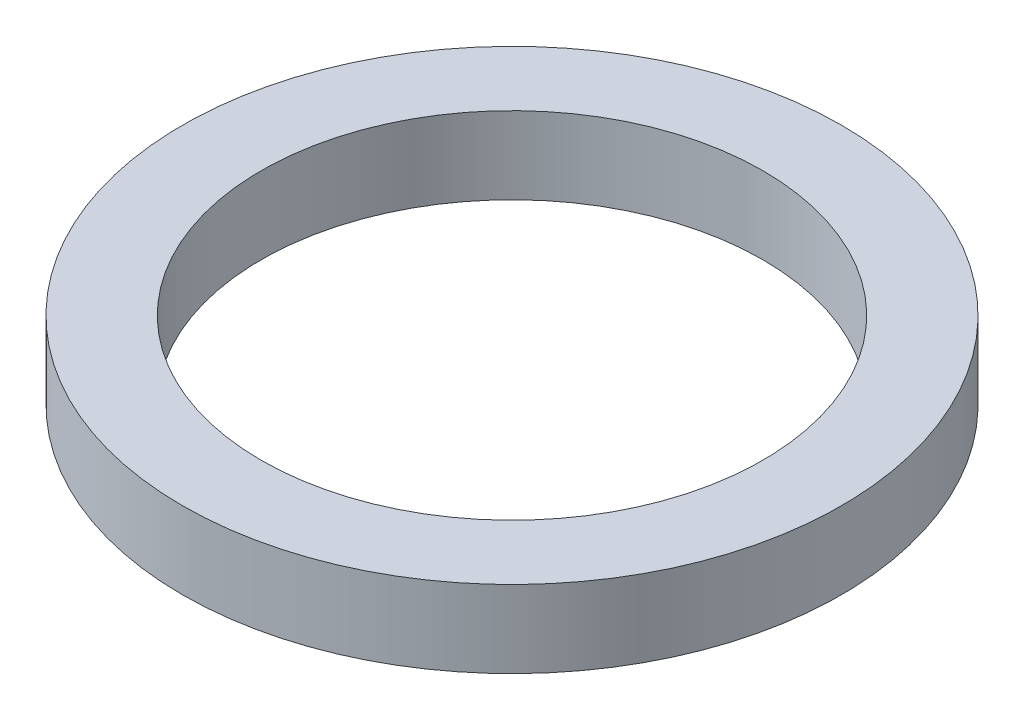
SolidWorks part; units mm, degrees
ref_plane "Front Plane" through (0, 0, 0) normal (0, 0, 1) x (1, 0, 0)
ref_plane "Top Plane" through (0, 0, 0) normal (0, 1, 0) x (1, 0, 0)
ref_plane "Right Plane" through (0, 0, 0) normal (1, 0, 0) x (0, 0, -1)
sketch "Sketch1" plane through (0, 0, 0) normal (0, 1, 0) x (1, 0, 0)
  circle A0 centre (0, 0) radius 20.6375
  circle A1 centre (0, 0) radius 27.1145
  dimension "D1" = 54.229
  dimension "D2" = 41.275
extrude "Boss-Extrude1" add sketch "Sketch1" along normal blind 6.35
